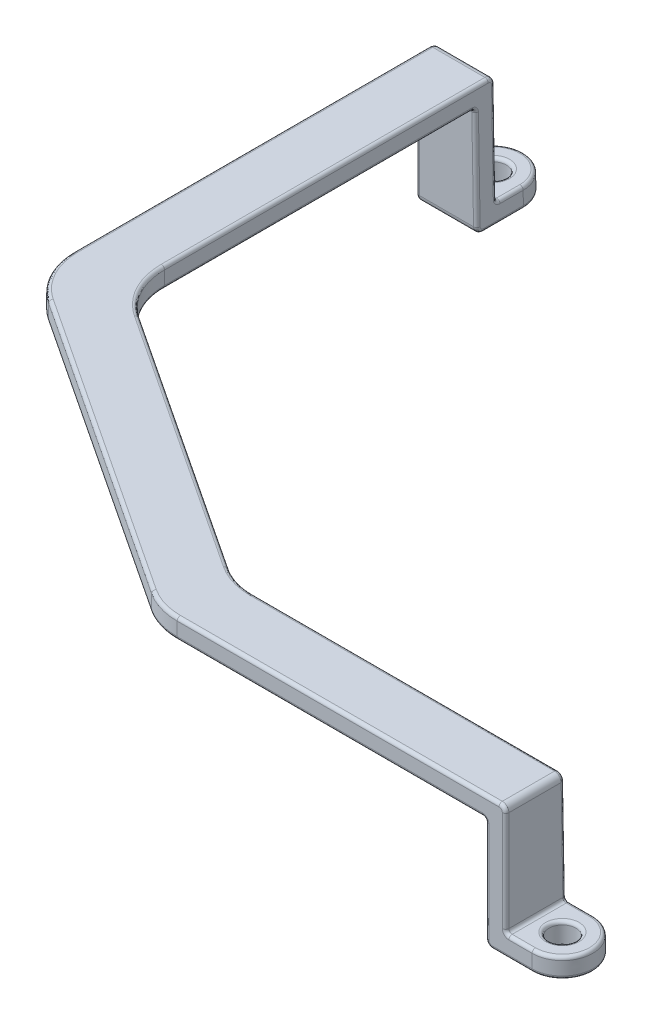
SolidWorks part; units mm, degrees
ref_plane "Front" through (0, 0, 0) normal (0, 0, 1) x (1, 0, 0)
ref_plane "Top" through (0, 0, 0) normal (0, 1, 0) x (1, 0, 0)
ref_plane "Right" through (0, 0, 0) normal (1, 0, 0) x (0, 0, -1)
sketch "Sketch1" plane through (0, 0, 0) normal (0, 1, 0) x (1, 0, 0)
  line L0 (-9.6, 6.3353) -> (13.6, -8.975)
  line L1 (-9.6, 6.3353) -> (-9.6, 35.975)
  line L2 (-14.2, 35.975) -> (-14.2, 3.8596)
  line L3 (40.6, -8.975) -> (13.6, -8.975)
  line L4 (12.219, -13.575) -> (40.6, -13.575)
  line L5 (-14.2, 3.8596) -> (12.219, -13.575)
  arc A1 (-9.6, 35.975) -> (-14.2, 35.975) centre (-11.9, 35.975) ccw
  arc A3 (40.6, -13.575) -> (40.6, -8.975) centre (40.6, -11.275) ccw
  circle A4 centre (-11.9, 35.975) radius 1
  circle A5 centre (40.6, -11.275) radius 1
extrude "Boss-Extrude1" add sketch "Sketch1" along normal blind 9.75 draft 0.5
sketch "Sketch3" plane through (0, 0, 0) normal (1, 0, 0) x (0, 0, -1)
  line L0 (41.5961, 1.5) -> (33.975, 1.5)
  line L3 (33.975, 1.5) -> (33.8915, 11.0737)
  line L4 (33.8915, 11.0737) -> (41.5961, 11.0737)
  line L5 (41.5961, 11.0737) -> (41.5961, 1.5)
  line L12 (35.975, 0) -> (3.8596, 0) construction
  line L14 (32.475, 0) -> (32.403, 8.25)
  line L17 (27.4064, 8.25) -> (32.403, 8.25)
  line L18 (27.4064, 8.25) -> (-15.5842, 8.25)
  line L19 (-15.5842, 8.25) -> (-15.5842, -1.4763)
  line L20 (-15.5842, -1.4763) -> (32.475, -1.4763)
  line L21 (32.475, -1.4763) -> (32.475, 0)
extrude "Cut-Extrude1" cut sketch "Sketch3" against normal blind 55.75
sketch "Sketch4" plane through (0, 0, 0) normal (0, 0, 1) x (1, 0, 0)
  line L2 (12.219, 0) -> (40.6, 0) construction
  line L3 (38.6, 1.5) -> (38.5083, 12.0074)
  line L4 (38.6, 1.5) -> (43.7246, 1.5)
  line L5 (43.7246, 1.5) -> (43.7246, 10.8363)
  line L6 (43.7246, 10.8363) -> (38.5083, 12.0074)
  line L8 (37.1, 0) -> (37.028, 8.25)
  line L9 (-4.5024, -4.924) -> (37.1, -4.924)
  line L11 (-4.5024, 8.25) -> (37.028, 8.25)
  line L12 (-4.5024, 8.25) -> (-4.5024, -4.924)
  line L13 (37.1, -4.924) -> (37.1, 0)
extrude "Cut-Extrude2" cut sketch "Sketch4" against normal mid plane 55.75
fillet "Fillet1" radius 5 4 edges at (13.5764, 9, 9.0535) (12.2426, 9, 13.4965) (-9.6785, 9, -6.293) (-14.1215, 9, -3.9019)
fillet "Fillet2" radius 0.5 2 edges at (-11.9, 9.75, -33.903) (38.528, 9.75, 11.275)
fillet "Fillet3" radius 0.25 2 edges at (-11.9, 8.25, -32.403) (37.028, 8.25, 11.275)
fillet "Fillet4" radius 0.5 2 edges at (37.1, 0, 11.275) (-11.9, 0, -32.475)
fillet "Fillet5" radius 0.25 2 edges at (-11.9, 1.5, -33.975) (38.6, 1.5, 11.275)
fillet "Fillet6" radius 0.25 56 edges at (-11.9, 1.5, -38.2619) (-14.1869, 1.5, -35.0989) (-14.1863, 1.5725, -34.0468) (-14.152, 5.5011, -33.9401) (-14.1162, 9.6051, -33.7594) (-14.1149, 9.75, -20.0018) (-13.5178, 9.75, -4.2268) (-0.4387, 9.75, 5.1199) (12.3079, 9.75, 13.2788) (25.889, 9.75, 13.4899) (38.3844, 9.6051, 13.4912) (38.5651, 5.5011, 13.527) (38.6718, 1.5725, 13.5613) (39.7239, 1.5, 13.5619) (42.8869, 1.5, 11.275) (39.7239, 1.5, 8.9881) (38.6718, 1.5725, 8.9887) (38.5651, 5.5011, 9.023) (38.3844, 9.6051, 9.0588) (26.5539, 9.75, 9.0601) (13.6378, 9.75, 8.8489) (2.4412, 9.75, 1.713) (-9.088, 9.75, -6.6109) (-9.0749, 8.25, -6.6179) (2.4497, 8.25, 1.7029) (13.6418, 8.25, 8.8358) (25.9298, 8.25, 9.047) (36.9562, 8.1775, 9.0464) (37.0629, 4.2489, 9.0121) (37.2436, 0.1449, 8.9763) (39.0978, 0, 8.975) (42.9, 0, 11.275) (39.0978, 0, 13.575) (37.2436, 0.1449, 13.5737) (37.0629, 4.2489, 13.5379) (36.9562, 8.1775, 13.5036) (25.2609, 8.25, 13.503) (12.304, 8.25, 13.2918) (-0.4472, 8.25, 5.13) (-13.5309, 8.25, -4.2197) (-14.128, 8.25, -19.3722) (-14.1286, 8.1775, -32.3312) (-14.1629, 4.2489, -32.4379) (-14.1987, 0.1449, -32.6186) (-14.2, 0, -34.4728) (-11.9, 0, -38.275) (-9.6714, 8.1775, -32.3312) (-9.672, 8.25, -20.5713) (-9.6851, 9.75, -21.1939) (-9.6838, 9.6051, -33.7594) (-9.648, 5.5011, -33.9401) (-9.6137, 1.5725, -34.0468) (-9.6131, 1.5, -35.0989) (-9.6, 0, -34.4728) (-9.6013, 0.1449, -32.6186) (-9.6371, 4.2489, -32.4379)
fillet "Fillet7" radius 0.25 2 edges at (40.6, 1.5, 10.2619) (-11.9, 1.5, -36.9881)
